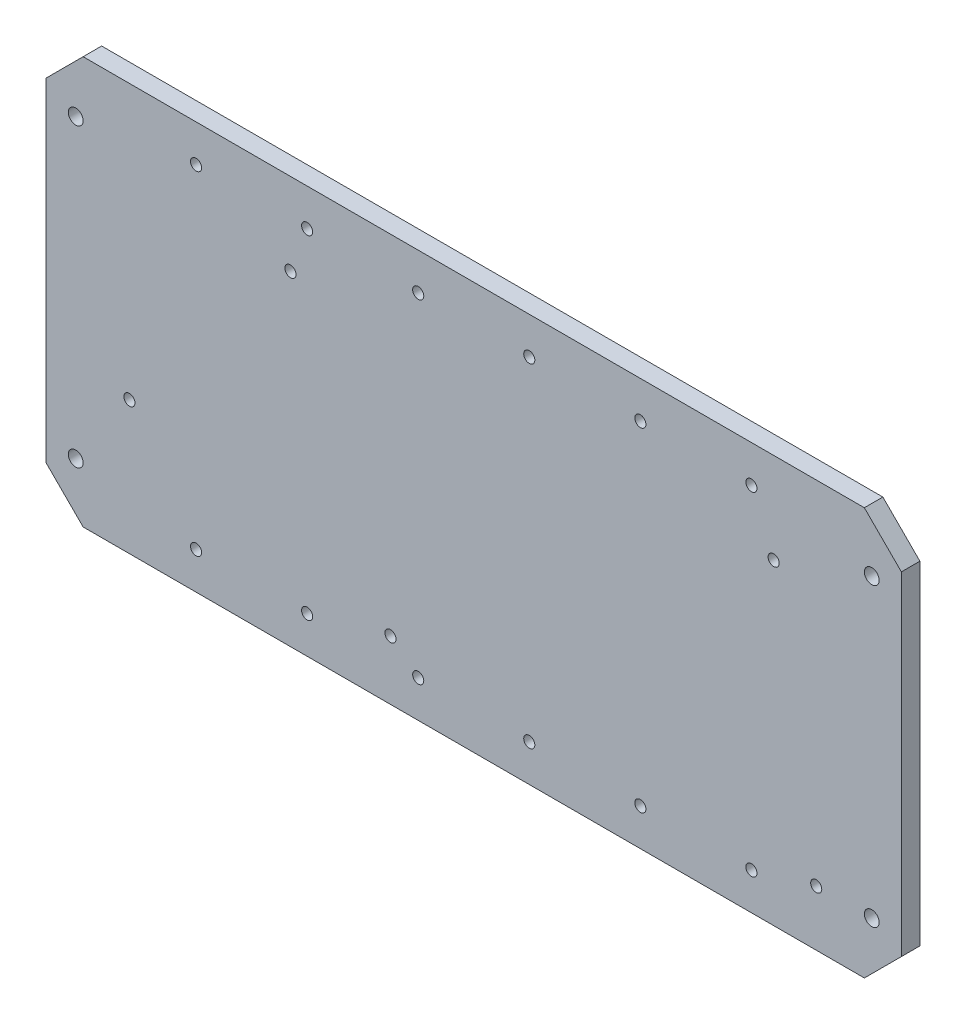
SolidWorks part; units mm, degrees
ref_plane "Front Plane" through (0, 0, 0) normal (0, 0, 1) x (1, 0, 0)
ref_plane "Top Plane" through (0, 0, 0) normal (0, 1, 0) x (1, 0, 0)
ref_plane "Right Plane" through (0, 0, 0) normal (1, 0, 0) x (0, 0, -1)
sketch "Sketch1" plane through (0, 0, 0) normal (0, 0, 1) x (1, 0, 0)
  line L0 (115.5, 110) -> (115.5, -20.1333) construction
  line L1 (0, 0) -> (231, 0)
  line L2 (0, 0) -> (0, 110)
  line L3 (0, 110) -> (231, 110)
  line L4 (231, 0) -> (231, 110)
  line L5 (201, 12) -> (91, 12) construction
  line L6 (201, 12) -> (201, 90) construction
  line L7 (201, 90) -> (91, 90) construction
  line L8 (91, 12) -> (91, 90) construction
  line L9 (73.5, 90) -> (20, 90) construction
  line L10 (73.5, 90) -> (73.5, 21) construction
  line L11 (73.5, 21) -> (20, 21) construction
  line L12 (20, 90) -> (20, 21) construction
  line L13 (0, 55) -> (-61.7257, 55) construction
  circle A0 centre (196.5, 85.5) radius 1.5
  circle A1 centre (93, 16) radius 1.5
  circle A2 centre (66, 87.8) radius 1.5
  circle A3 centre (22.5, 36) radius 1.5
  circle A4 centre (223, 95) radius 2
  circle A5 centre (223, 15) radius 2
  circle A6 centre (8, 95) radius 2
  circle A7 centre (8, 15) radius 2
  circle A8 centre (208, 15) radius 1.5
  circle A9 centre (130.5, 100) radius 1.5
  circle A10 centre (160.5, 100) radius 1.5
  circle A11 centre (190.5, 100) radius 1.5
  circle A12 centre (40.5, 100) radius 1.5
  circle A13 centre (70.5, 100) radius 1.5
  circle A14 centre (100.5, 100) radius 1.5
  circle A15 centre (100.5, 10) radius 1.5
  circle A16 centre (70.5, 10) radius 1.5
  circle A17 centre (40.5, 10) radius 1.5
  circle A18 centre (190.5, 10) radius 1.5
  circle A19 centre (160.5, 10) radius 1.5
  circle A20 centre (130.5, 10) radius 1.5
  dimension "D7" = 3
  dimension "D10" = 3
  dimension "D18" = 3
  dimension "D22" = 3
  dimension "D24" = 4
  dimension "D27" = 4
  dimension "D28" = 3
  dimension "D30" = 3
  dimension "D32" = 10
  dimension "D1" = 231
  dimension "D2" = 110
  dimension "D3" = 110
  dimension "D4" = 78
  dimension "D5" = 30
  dimension "D6" = 20
  dimension "D8" = 4.5
  dimension "D9" = 4.5
  dimension "D11" = 2
  dimension "D12" = 4
  dimension "D13" = 53.5
  dimension "D14" = 69
  dimension "D15" = 20
  dimension "D16" = 20
  dimension "D17" = 2.2
  dimension "D19" = 7.5
  dimension "D20" = 15
  dimension "D21" = 2.5
  dimension "D23" = 107.5
  dimension "D25" = 15
  dimension "D26" = 15
  dimension "D29" = 15
  dimension "D31" = 15
  dimension "D33" = 3
extrude "Boss-Extrude1" add sketch "Sketch1" along normal blind 5
chamfer "Chamfer1" distance 10 angle 45 4 edges at (0, 0, 2.5) (231, 0, 2.5) (231, 110, 2.5) (0, 110, 2.5)
